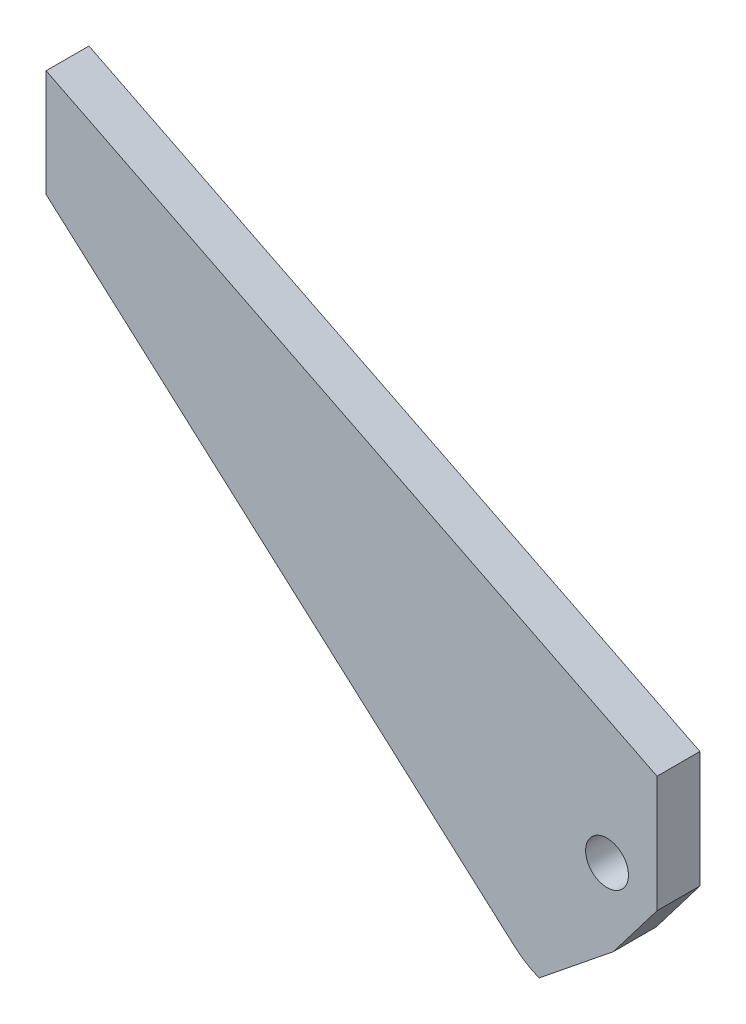
SolidWorks part; units mm, degrees
ref_plane "Front Plane" through (0, 0, 0) normal (0, 0, 1) x (1, 0, 0)
ref_plane "Top Plane" through (0, 0, 0) normal (0, 1, 0) x (1, 0, 0)
ref_plane "Right Plane" through (0, 0, 0) normal (1, 0, 0) x (0, 0, -1)
sketch "Sketch1" plane through (0, 0, 0) normal (0, 0, 1) x (1, 0, 0)
  line L1 (2, 15) -> (2, 4.2016)
  line L14 (-16.7549, 7.5203) -> (-7.9887, -0.2806)
  line L26 (2, 15) -> (-40.7549, 36.3775)
  line L27 (-16.7549, 7.5203) -> (-40.7549, 28.8775)
  line L28 (-40.7549, 28.8775) -> (-40.7549, 36.3775)
  circle A0 centre (-1.5, 8) radius 1.5
  arc A1 (-7.9887, -0.2806) -> (2, 4.2016) centre (-4, 4.2016) ccw
  point P6 (-6, 4.7191)
  point P7 (2, 2.6772)
  point P8 (-12.2505, -2.3159)
  dimension "D7" = 3
  dimension "D10" = 12
  dimension "D2" = 42.7549
  dimension "D3" = 21.3775
  dimension "D4" = 21.3571
  dimension "D5" = 15
  dimension "D6" = 2
  dimension "D8" = 8
  dimension "D9" = 1.5
  dimension "D18" = 24
  dimension "D19" = 7.5
extrude "Boss-Extrude1" add sketch "Sketch1" along normal blind 3
sketch "Sketch2" plane through (0, 0, 3) normal (0, 0, 1) x (1, 0, 0)
  line L0 (-1.0617, 2.8324) -> (-6.53, -1.5787)
  line L1 (2, 4.2016) -> (2, 15) construction
  line L2 (-40.7549, 28.8775) -> (-7.9887, -0.2806) construction
  line L3 (-6.53, -1.5787) -> (-7.0791, -3.6275)
  line L4 (-7.0791, -3.6275) -> (6.6022, -3.9732)
  line L5 (6.6022, -3.9732) -> (4.4783, 4.339)
  line L7 (-1.0617, 2.8324) -> (2, 6.8454)
  line L8 (2, 6.8454) -> (4.4783, 4.339)
  point P0 (-1.0617, 2.8324)
  point P6 (-0.4443, 3.5578)
extrude "Cut-Extrude1" cut sketch "Sketch2" against normal blind 3
